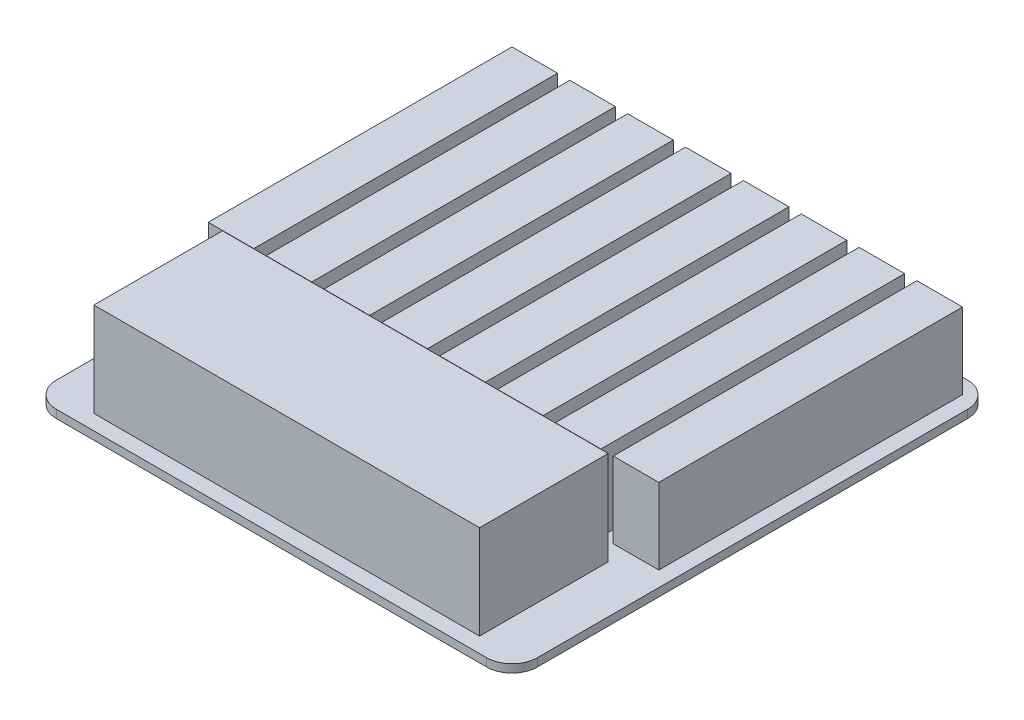
SolidWorks part; units mm, degrees
material "Kapton"
ref_plane "Front Plane" through (0, 0, 0) normal (0, 0, 1) x (1, 0, 0)
ref_plane "Top Plane" through (0, 0, 0) normal (0, 1, 0) x (1, 0, 0)
ref_plane "Right Plane" through (0, 0, 0) normal (1, 0, 0) x (0, 0, -1)
sketch "Sketch1" plane through (0, 0, 0) normal (0, 1, 0) x (1, 0, 0)
  line L1 (-47.5, -47.5) -> (47.5, -47.5)
  line L2 (-47.5, -47.5) -> (-47.5, 47.5)
  line L3 (-47.5, 47.5) -> (47.5, 47.5)
  line L4 (47.5, -47.5) -> (47.5, 47.5)
  line L5 (-47.5, -47.5) -> (47.5, 47.5) construction
  line L6 (-47.5, 47.5) -> (47.5, -47.5) construction
  point P0 (0, 0)
  dimension "D1" = 95
extrude "Boss-Extrude1" add sketch "Sketch1" along normal mid plane 1.6
fillet "Fillet1" radius 5 4 edges at (-47.5, 0, -47.5) (47.5, 0, -47.5) (-47.5, 0, 47.5) (47.5, 0, 47.5)
sketch "Sketch2" plane through (0, 0.8, 0) normal (0, 1, 0) x (1, 0, 0)
  line L0 (-42.5, -47.5) -> (42.5, -47.5) construction
  line L9 (-38.1, -44.5) -> (38.1, -44.5)
  line L10 (-38.1, -44.5) -> (-38.1, -19.1)
  line L11 (-38.1, -19.1) -> (38.1, -19.1)
  line L12 (38.1, -44.5) -> (38.1, -19.1)
  line L13 (-38.1, -44.5) -> (38.1, -19.1) construction
  line L14 (-38.1, -19.1) -> (38.1, -44.5) construction
  point P0 (0, -31.8)
  dimension "D1" = 25.4
  dimension "D2" = 76.2
  dimension "D3" = 3
extrude "Boss-Extrude2" add sketch "Sketch2" along normal blind 18.542
sketch "Sketch3" plane through (0, 0.8, 0) normal (0, 1, 0) x (1, 0, 0)
  line L0 (42.5, 47.5) -> (-42.5, 47.5) construction
  line L1 (-44.5, 44.5) -> (-35.5, 44.5)
  line L2 (-44.5, 44.5) -> (-44.5, -15.5)
  line L3 (-44.5, -15.5) -> (-35.5, -15.5)
  line L4 (-35.5, 44.5) -> (-35.5, -15.5)
  line L5 (-47.5, 42.5) -> (-47.5, -42.5) construction
  line L6 (44.5, 47.5) -> (44.5, -47.5) construction
  line L7 (-42.5, -47.5) -> (42.5, -47.5) construction
  line L8 (47.5, -42.5) -> (47.5, 42.5) construction
  line L10 (-33.0714, 44.5) -> (-33.0714, -15.5)
  line L11 (-33.0714, 44.5) -> (-24.0714, 44.5)
  line L12 (-24.0714, 44.5) -> (-24.0714, -15.5)
  line L13 (-33.0714, -15.5) -> (-24.0714, -15.5)
  line L14 (-21.6429, 44.5) -> (-21.6429, -15.5)
  line L15 (-21.6429, 44.5) -> (-12.6429, 44.5)
  line L16 (-12.6429, 44.5) -> (-12.6429, -15.5)
  line L17 (-21.6429, -15.5) -> (-12.6429, -15.5)
  line L18 (-10.2143, 44.5) -> (-10.2143, -15.5)
  line L19 (-10.2143, 44.5) -> (-1.2143, 44.5)
  line L20 (-1.2143, 44.5) -> (-1.2143, -15.5)
  line L21 (-10.2143, -15.5) -> (-1.2143, -15.5)
  line L22 (1.2143, 44.5) -> (1.2143, -15.5)
  line L23 (1.2143, 44.5) -> (10.2143, 44.5)
  line L24 (10.2143, 44.5) -> (10.2143, -15.5)
  line L25 (1.2143, -15.5) -> (10.2143, -15.5)
  line L26 (12.6429, 44.5) -> (12.6429, -15.5)
  line L27 (12.6429, 44.5) -> (21.6429, 44.5)
  line L28 (21.6429, 44.5) -> (21.6429, -15.5)
  line L29 (12.6429, -15.5) -> (21.6429, -15.5)
  line L30 (24.0714, 44.5) -> (24.0714, -15.5)
  line L31 (24.0714, 44.5) -> (33.0714, 44.5)
  line L32 (33.0714, 44.5) -> (33.0714, -15.5)
  line L33 (24.0714, -15.5) -> (33.0714, -15.5)
  line L34 (35.5, 44.5) -> (35.5, -15.5)
  line L35 (35.5, 44.5) -> (44.5, 44.5)
  line L36 (44.5, 44.5) -> (44.5, -15.5)
  line L37 (35.5, -15.5) -> (44.5, -15.5)
  dimension "D1" = 60
  dimension "D2" = 3
  dimension "D3" = 3
  dimension "D4" = 9
  dimension "D5" = 3
  dimension "D7" = 8
extrude "Boss-Extrude3" add sketch "Sketch3" along normal blind 15
